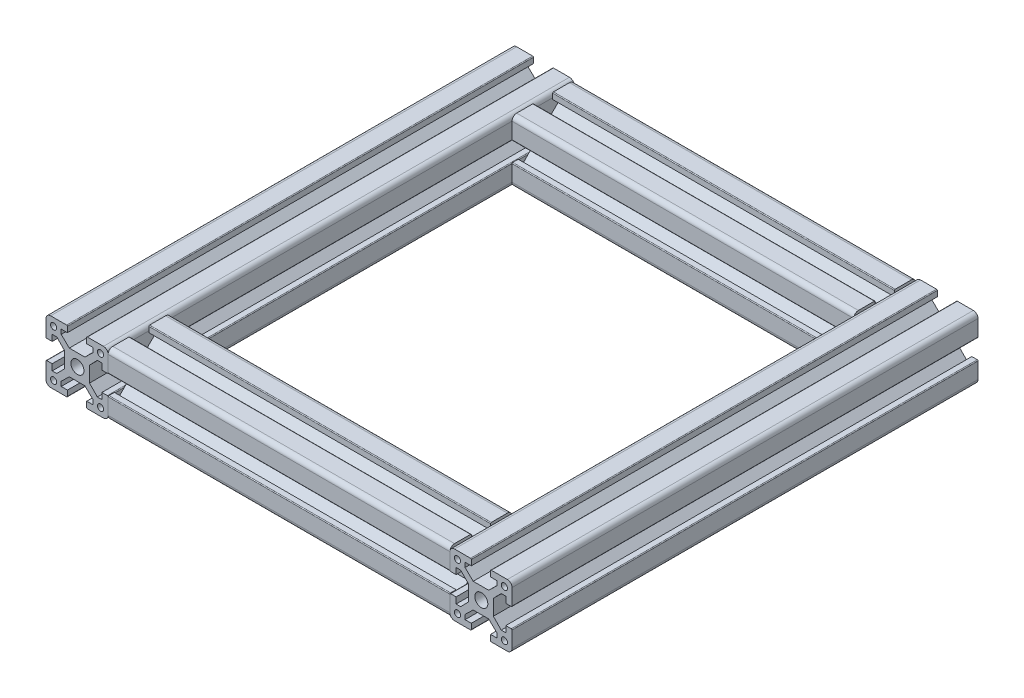
SolidWorks part; units mm, degrees
ref_plane "Front Plane" through (0, 0, 0) normal (0, 0, 1) x (1, 0, 0)
ref_plane "Top Plane" through (0, 0, 0) normal (0, 1, 0) x (1, 0, 0)
ref_plane "Right Plane" through (0, 0, 0) normal (1, 0, 0) x (0, 0, -1)
sketch "Sketch13" plane through (0, 0, 0) normal (0, 1, 0) x (1, 0, 0)
  line L0 (-65, 65) -> (65, -65) construction
  line L1 (-65, -65) -> (65, -65)
  line L2 (-65, -65) -> (-65, 65)
  line L3 (-65, 65) -> (65, 65)
  line L4 (65, -65) -> (65, 65)
  line L5 (-65, -65) -> (65, 65) construction
  point P0 (0, 0)
  dimension "D1" = 130
  dimension "D2" = 130
other "Xa XA-2020T(1)"
ref_plane "Plane3" through (-65, 0, 65) normal (0, 0, -1) x (-1, 0, 0)
sketch "Sketch1" plane through (-65, 0, 65) normal (0, 0, -1) x (-1, 0, 0)
  line L0 (-9.8891, 9.9394) -> (10.1109, -10.0606) construction
  line L1 (-9.8891, 9.9394) -> (10.1109, 9.9394) construction
  line L2 (-9.8891, 9.9394) -> (-9.8891, -10.0606) construction
  line L3 (-9.8891, -10.0606) -> (10.1109, -10.0606) construction
  line L4 (10.1109, 9.9394) -> (10.1109, -10.0606) construction
  line L5 (-9.8891, -10.0606) -> (10.1109, 9.9394) construction
  line L6 (0.1109, 9.9394) -> (0.1109, -10.0606) construction
  line L7 (10.1109, -0.0606) -> (-9.8891, -0.0606) construction
  line L88 (-9.8891, 8.4394) -> (-9.8891, 3.2894)
  line L89 (-9.6391, 3.0394) -> (-7.8891, 3.0394)
  line L90 (-7.8891, 3.0394) -> (-7.8891, 5.0394)
  line L91 (-7.8891, 5.0394) -> (-6.4169, 5.0394)
  line L92 (-6.4169, 5.0394) -> (-3.8891, 2.4394)
  line L93 (-3.8891, 2.4394) -> (-3.8891, -2.5606)
  line L94 (-3.8891, -2.5606) -> (-6.4169, -5.1606)
  line L95 (-6.4169, -5.1606) -> (-7.8891, -5.1606)
  line L96 (-7.8891, -5.1606) -> (-7.8891, -3.1606)
  line L97 (-7.8891, -3.1606) -> (-9.6391, -3.1606)
  line L98 (-9.8891, -3.4106) -> (-9.8891, -8.5606)
  line L99 (-8.3891, -10.0606) -> (-3.2391, -10.0606)
  line L100 (-2.9891, -9.8106) -> (-2.9891, -8.0606)
  line L101 (-2.9891, -8.0606) -> (-4.9891, -8.0606)
  line L102 (-4.9891, -8.0606) -> (-4.9891, -6.5883)
  line L103 (-4.9891, -6.5883) -> (-2.3891, -4.0606)
  line L104 (-2.3891, -4.0606) -> (2.6109, -4.0606)
  line L105 (2.6109, -4.0606) -> (5.2109, -6.5883)
  line L106 (5.2109, -6.5883) -> (5.2109, -8.0606)
  line L107 (5.2109, -8.0606) -> (3.2109, -8.0606)
  line L108 (3.2109, -8.0606) -> (3.2109, -9.8106)
  line L109 (3.4609, -10.0606) -> (8.6109, -10.0606)
  line L110 (10.1109, -8.5606) -> (10.1109, -3.4106)
  line L111 (9.8609, -3.1606) -> (8.1109, -3.1606)
  line L112 (8.1109, -3.1606) -> (8.1109, -5.1606)
  line L113 (8.1109, -5.1606) -> (6.6387, -5.1606)
  line L114 (6.6387, -5.1606) -> (4.1109, -2.5606)
  line L115 (4.1109, -2.5606) -> (4.1109, 2.4394)
  line L116 (4.1109, 2.4394) -> (6.6387, 5.0394)
  line L117 (6.6387, 5.0394) -> (8.1109, 5.0394)
  line L118 (8.1109, 5.0394) -> (8.1109, 3.0394)
  line L119 (8.1109, 3.0394) -> (9.8609, 3.0394)
  line L120 (10.1109, 3.2894) -> (10.1109, 8.4394)
  line L121 (8.6109, 9.9394) -> (3.4609, 9.9394)
  line L122 (3.2109, 9.6894) -> (3.2109, 7.9394)
  line L123 (3.2109, 7.9394) -> (5.2109, 7.9394)
  line L124 (5.2109, 7.9394) -> (5.2109, 6.4672)
  line L125 (5.2109, 6.4672) -> (2.6109, 3.9394)
  line L126 (2.6109, 3.9394) -> (-2.3891, 3.9394)
  line L127 (-2.3891, 3.9394) -> (-4.9891, 6.4672)
  line L128 (-4.9891, 6.4672) -> (-4.9891, 7.9394)
  line L129 (-4.9891, 7.9394) -> (-2.9891, 7.9394)
  line L130 (-2.9891, 7.9394) -> (-2.9891, 9.6894)
  line L131 (-3.2391, 9.9394) -> (-8.3891, 9.9394)
  circle A0 centre (-7.4391, 7.4894) radius 1
  circle A1 centre (7.6609, 7.4894) radius 1
  circle A2 centre (-7.4391, -7.6106) radius 1
  circle A3 centre (7.6609, -7.6106) radius 1
  circle A4 centre (0, 0) radius 2.1
  arc A26 (-9.8891, 3.2894) -> (-9.6391, 3.0394) centre (-9.6391, 3.2894) ccw
  arc A27 (-9.6391, -3.1606) -> (-9.8891, -3.4106) centre (-9.6391, -3.4106) ccw
  arc A28 (-9.8891, -8.5606) -> (-8.3891, -10.0606) centre (-8.3891, -8.5606) ccw
  arc A29 (-3.2391, -10.0606) -> (-2.9891, -9.8106) centre (-3.2391, -9.8106) ccw
  arc A30 (3.2109, -9.8106) -> (3.4609, -10.0606) centre (3.4609, -9.8106) ccw
  arc A31 (8.6109, -10.0606) -> (10.1109, -8.5606) centre (8.6109, -8.5606) ccw
  arc A32 (10.1109, -3.4106) -> (9.8609, -3.1606) centre (9.8609, -3.4106) ccw
  arc A33 (9.8609, 3.0394) -> (10.1109, 3.2894) centre (9.8609, 3.2894) ccw
  arc A34 (10.1109, 8.4394) -> (8.6109, 9.9394) centre (8.6109, 8.4394) ccw
  arc A35 (3.4609, 9.9394) -> (3.2109, 9.6894) centre (3.4609, 9.6894) ccw
  arc A36 (-2.9891, 9.6894) -> (-3.2391, 9.9394) centre (-3.2391, 9.6894) ccw
  arc A37 (-8.3891, 9.9394) -> (-9.8891, 8.4394) centre (-8.3891, 8.4394) ccw
  point P52 (0, 0)
